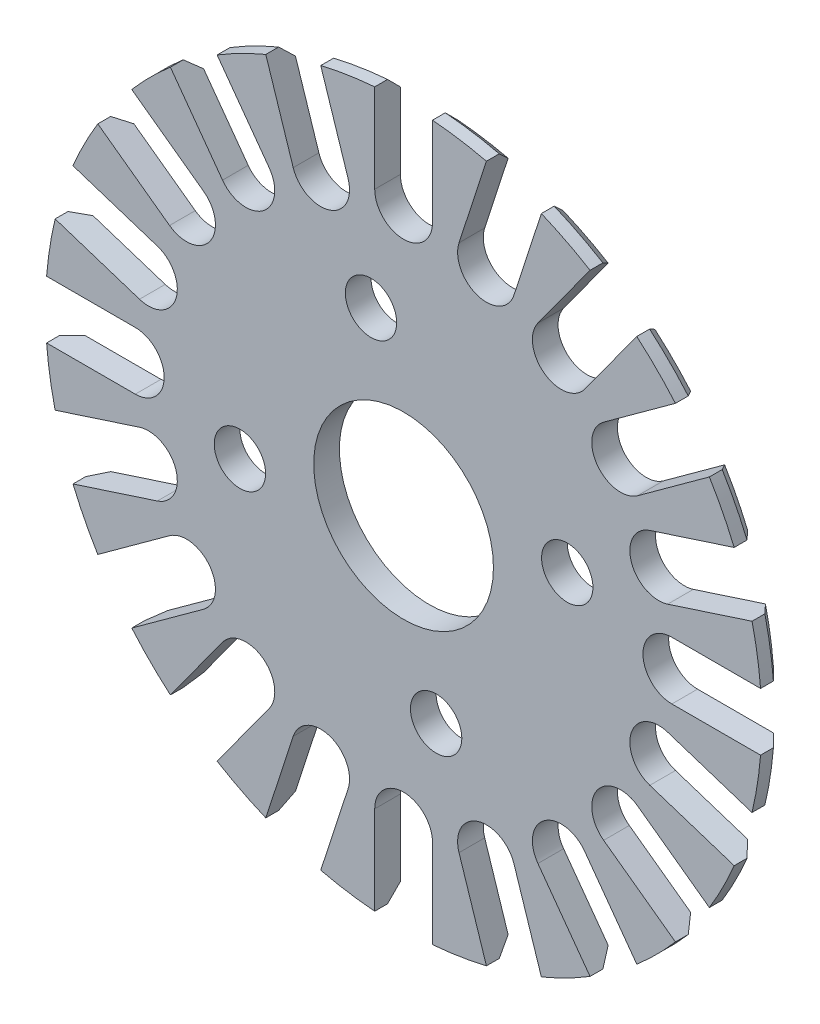
SolidWorks part; units mm, degrees
material "2A12"
ref_plane "前视基准面" through (0, 0, 0) normal (0, 0, 1) x (1, 0, 0)
ref_plane "上视基准面" through (0, 0, 0) normal (0, 1, 0) x (1, 0, 0)
ref_plane "右视基准面" through (0, 0, 0) normal (1, 0, 0) x (0, 0, -1)
sketch "草图1" plane through (0, 0, 0) normal (0, 0, 1) x (1, 0, 0)
  circle A0 centre (0, 0) radius 27.9
  dimension "D1" = 55.8
extrude "拉伸1" add sketch "草图1" along normal blind 2
sketch "草图2" plane through (0, 0, 2) normal (0, 0, 1) x (1, 0, 0)
  circle A0 centre (0, 0) radius 7
  dimension "D1" = 14
extrude "拉伸2" cut sketch "草图2" against normal blind 3
sketch "草图3" plane through (0, 0, 2) normal (0, 0, 1) x (1, 0, 0)
  line L0 (-2.5362, 12.7502) -> (0, 0) construction
  line L1 (0, 0) -> (0, 13) construction
  circle A0 centre (-2.5362, 12.7502) radius 2
  circle A1 centre (0, 0) radius 13 construction
  dimension "D1" = 26
  dimension "D2" = 4
  dimension "D3" = 11.25
extrude "拉伸3" cut sketch "草图3" against normal blind 3
pattern_circular "阵列(圆周)1" count 4 every 90 about axis through (0, 0, 0) along (0, 0, 1) of "拉伸3"
chamfer "倒角1" distance 1 angle 45 1 edges at (27.9, 0, 0)
sketch "草图4" plane through (0, 0, 2) normal (0, 0, 1) x (1, 0, 0)
  line L0 (-20.9, 2.25) -> (-27.8091, 2.25)
  line L1 (-20.9, -2.25) -> (-27.8091, -2.25)
  circle A0 centre (0, 0) radius 20.9 construction
  arc A1 (-20.9, -2.25) -> (-20.9, 2.25) centre (-20.9, 0) ccw
  circle A2 centre (0, 0) radius 27.9 construction
  arc A4 (-27.8091, 2.25) -> (-27.8091, -2.25) centre (0, 0) ccw
  dimension "D1" = 41.8
  dimension "D2" = 4.5
extrude "拉伸4" cut sketch "草图4" against normal blind 3
pattern_circular "阵列(圆周)3" count 20 over 360 about axis through (0, 0, 0) along (0, 0, 1) of "拉伸4"
